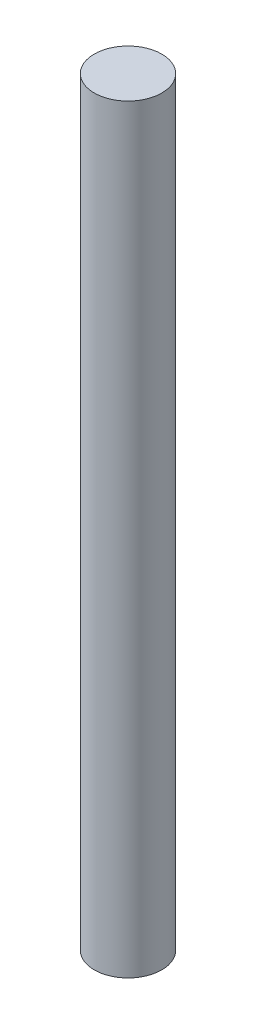
SolidWorks part; units mm, degrees
ref_plane "Front Plane" through (0, 0, 0) normal (0, 0, 1) x (1, 0, 0)
ref_plane "Top Plane" through (0, 0, 0) normal (0, 1, 0) x (1, 0, 0)
ref_plane "Right Plane" through (0, 0, 0) normal (1, 0, 0) x (0, 0, -1)
sketch "Sketch1" plane through (0, 0, 0) normal (0, 1, 0) x (1, 0, 0)
  circle A0 centre (0, 0) radius 2
  dimension "D1" = 4
extrude "Boss-Extrude1" add sketch "Sketch1" along normal blind 45
